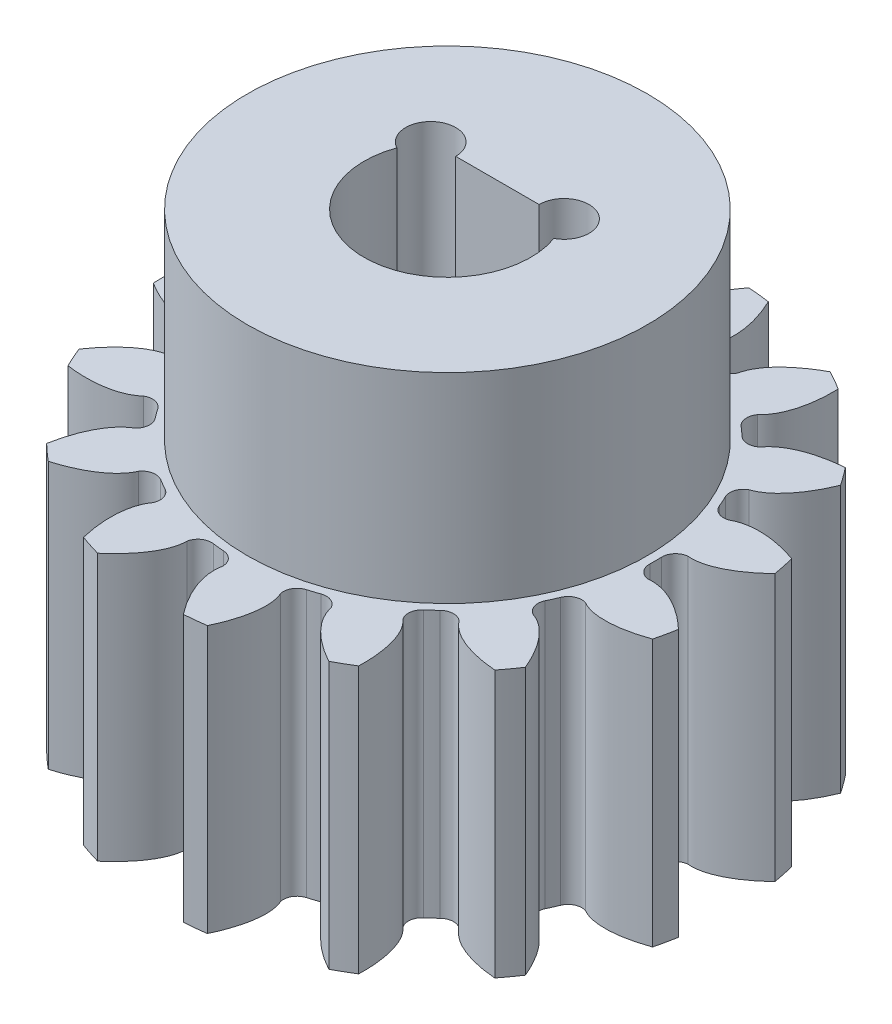
SolidWorks part; units mm, degrees
ref_plane "Front Plane" through (0, 0, 0) normal (0, 0, 1) x (1, 0, 0)
ref_plane "Top Plane" through (0, 0, 0) normal (0, 1, 0) x (1, 0, 0)
ref_plane "Right Plane" through (0, 0, 0) normal (1, 0, 0) x (0, 0, -1)
ref_plane "Plane1" through (0, -8, 0) normal (0, -1, 0) x (1, 0, 0)
sketch "Sketch1" plane through (0, -8, 0) normal (0, -1, 0) x (1, 0, 0)
  arc A0 (-0.8279, 6.1949) -> (-1.2849, 6.5225) centre (-0.8822, 6.6017) cw
  arc A1 (-2.3127, 8.1793) -> (-2.9366, 7.9766) centre (0, 0) ccw
  arc A2 (-2.7943, 6.0321) -> (-2.9715, 5.4984) centre (-3.1666, 5.8594) cw
  arc A3 (-2.9715, 5.4984) -> (-3.276, 5.3226) centre (0, 0) ccw
  arc A4 (-3.276, 5.3226) -> (-3.8268, 5.436) centre (-3.4911, 5.6721) cw
  arc A5 (-5.4396, 6.5315) -> (-5.9271, 6.0925) centre (0, 0) ccw
  arc A6 (-5.0062, 4.374) -> (-4.951, 3.8144) centre (-5.2761, 4.0649) cw
  arc A7 (-4.951, 3.8144) -> (-5.1577, 3.53) centre (0, 0) ccw
  arc A8 (-5.1577, 3.53) -> (-5.7069, 3.4095) centre (-5.4963, 3.7618) cw
  arc A9 (-7.6259, 3.7543) -> (-7.8928, 3.155) centre (0, 0) ccw
  arc A10 (-6.3525, 1.9596) -> (-6.0745, 1.4709) centre (-6.4733, 1.5675) cw
  arc A11 (-6.0745, 1.4709) -> (-6.1476, 1.127) centre (0, 0) ccw
  arc A12 (-6.1476, 1.127) -> (-6.6003, 0.7936) centre (-6.5512, 1.201) cw
  arc A13 (-8.4937, 0.328) -> (-8.4937, -0.328) centre (0, 0) ccw
  arc A14 (-6.6003, -0.7936) -> (-6.1476, -1.127) centre (-6.5512, -1.201) cw
  arc A15 (-6.1476, -1.127) -> (-6.0745, -1.4709) centre (0, 0) ccw
  arc A16 (-6.0745, -1.4709) -> (-6.3525, -1.9596) centre (-6.4733, -1.5675) cw
  arc A17 (-7.8928, -3.155) -> (-7.6259, -3.7543) centre (0, 0) ccw
  arc A18 (-5.7069, -3.4095) -> (-5.1577, -3.53) centre (-5.4963, -3.7618) cw
  arc A19 (-5.1577, -3.53) -> (-4.951, -3.8144) centre (0, 0) ccw
  arc A20 (-4.951, -3.8144) -> (-5.0062, -4.374) centre (-5.2761, -4.0649) cw
  arc A21 (-5.9271, -6.0925) -> (-5.4396, -6.5315) centre (0, 0) ccw
  arc A22 (-3.8268, -5.436) -> (-3.276, -5.3226) centre (-3.4911, -5.6721) cw
  arc A23 (-3.276, -5.3226) -> (-2.9715, -5.4984) centre (0, 0) ccw
  arc A24 (-2.9715, -5.4984) -> (-2.7943, -6.0321) centre (-3.1666, -5.8594) cw
  arc A25 (-2.9366, -7.9766) -> (-2.3127, -8.1793) centre (0, 0) ccw
  arc A26 (-1.2849, -6.5225) -> (-0.8279, -6.1949) centre (-0.8822, -6.6017) cw
  arc A27 (-0.8279, -6.1949) -> (-0.4782, -6.2317) centre (0, 0) ccw
  arc A28 (-0.4782, -6.2317) -> (-0.0993, -6.6471) centre (-0.5096, -6.6408) cw
  arc A29 (0.5616, -8.4814) -> (1.214, -8.4129) centre (0, 0) ccw
  arc A30 (1.4791, -6.4812) -> (1.7634, -5.9961) centre (1.8792, -6.3898) cw
  arc A31 (1.7634, -5.9961) -> (2.0978, -5.8874) centre (0, 0) ccw
  arc A32 (2.0978, -5.8874) -> (2.6129, -6.1128) centre (2.2355, -6.274) cw
  arc A33 (3.9628, -7.5197) -> (4.5309, -7.1917) centre (0, 0) ccw
  arc A34 (3.9874, -5.3193) -> (4.0498, -4.7605) centre (4.3157, -5.073) cw
  arc A35 (4.0498, -4.7605) -> (4.3111, -4.5252) centre (0, 0) ccw
  arc A36 (4.3111, -4.5252) -> (4.8733, -4.5216) centre (4.5941, -4.8223) cw
  arc A37 (6.6787, -5.2578) -> (7.0643, -4.7271) centre (0, 0) ccw
  arc A38 (5.8062, -3.2376) -> (5.6359, -2.7017) centre (6.0059, -2.8791) cw
  arc A39 (5.6359, -2.7017) -> (5.7789, -2.3805) centre (0, 0) ccw
  arc A40 (5.7789, -2.3805) -> (6.2911, -2.1485) centre (6.1583, -2.5368) cw
  arc A41 (8.2399, -2.0868) -> (8.3763, -1.4451) centre (0, 0) ccw
  arc A42 (6.6211, -0.5961) -> (6.2475, -0.1758) centre (6.6577, -0.1873) cw
  arc A43 (6.2475, -0.1758) -> (6.2475, 0.1758) centre (0, 0) ccw
  arc A44 (6.2475, 0.1758) -> (6.6211, 0.5961) centre (6.6577, 0.1873) cw
  arc A45 (8.3763, 1.4451) -> (8.2399, 2.0868) centre (0, 0) ccw
  arc A46 (6.2911, 2.1485) -> (5.7789, 2.3805) centre (6.1583, 2.5368) cw
  arc A47 (5.7789, 2.3805) -> (5.6359, 2.7017) centre (0, 0) ccw
  arc A48 (5.6359, 2.7017) -> (5.8062, 3.2376) centre (6.0059, 2.8791) cw
  arc A49 (7.0643, 4.7271) -> (6.6787, 5.2578) centre (0, 0) ccw
  arc A50 (4.8733, 4.5216) -> (4.3111, 4.5252) centre (4.5941, 4.8223) cw
  arc A51 (4.3111, 4.5252) -> (4.0498, 4.7605) centre (0, 0) ccw
  arc A52 (4.0498, 4.7605) -> (3.9874, 5.3193) centre (4.3157, 5.073) cw
  arc A53 (4.5309, 7.1917) -> (3.9628, 7.5197) centre (0, 0) ccw
  arc A54 (2.6129, 6.1128) -> (2.0978, 5.8874) centre (2.2355, 6.274) cw
  arc A55 (2.0978, 5.8874) -> (1.7634, 5.9961) centre (0, 0) ccw
  arc A56 (1.7634, 5.9961) -> (1.4791, 6.4812) centre (1.8792, 6.3898) cw
  arc A57 (1.214, 8.4129) -> (0.5616, 8.4814) centre (0, 0) ccw
  arc A58 (-0.0993, 6.6471) -> (-0.4782, 6.2317) centre (-0.5096, 6.6408) cw
  arc A59 (-0.4782, 6.2317) -> (-0.8279, 6.1949) centre (0, 0) ccw
  ellipse E0 centre (-3.7721, 7.5173) end of major axis (-6.1606, 8.8992) minor radius 1.3852 (-1.2849, 6.5225) -> (-2.3127, 8.1793) ccw
  ellipse E1 centre (-1.3668, 8.2988) end of major axis (-0.2467, 10.8207) minor radius 1.3852 (-2.9366, 7.9766) -> (-2.7943, 6.0321) ccw
  ellipse E2 centre (-6.5036, 5.3331) end of major axis (-9.2477, 5.624) minor radius 1.3852 (-3.8268, 5.436) -> (-5.4396, 6.5315) ccw
  ellipse E3 centre (-4.6241, 7.0254) end of major axis (-4.6266, 9.7849) minor radius 1.3852 (-5.9271, 6.0925) -> (-5.0062, 4.374) ccw
  ellipse E4 centre (-8.1105, 2.2268) end of major axis (-5.4853, 3.0772) minor radius 1.3852 (-5.7069, 3.4095) -> (-7.6259, 3.7543) ccw
  ellipse E5 centre (-7.0818, 4.5372) end of major axis (-8.2065, 7.0571) minor radius 1.3852 (-7.8928, 3.155) -> (-6.3525, 1.9596) ccw
  ellipse E6 centre (-8.315, -1.2645) end of major axis (-6.2627, 0.5801) minor radius 1.3852 (-6.6003, 0.7936) -> (-8.4937, 0.328) ccw
  ellipse E7 centre (-8.315, 1.2645) end of major axis (-10.3674, 3.1091) minor radius 1.3852 (-8.4937, -0.328) -> (-6.6003, -0.7936) ccw
  ellipse E8 centre (-7.0818, -4.5372) end of major axis (-8.2065, -7.0571) minor radius 1.3852 (-6.3525, -1.9596) -> (-7.8928, -3.155) ccw
  ellipse E9 centre (-8.1105, -2.2268) end of major axis (-10.7357, -1.3765) minor radius 1.3852 (-7.6259, -3.7543) -> (-5.7069, -3.4095) ccw
  ellipse E10 centre (-4.6241, -7.0254) end of major axis (-4.6266, -9.7849) minor radius 1.3852 (-5.0062, -4.374) -> (-5.9271, -6.0925) ccw
  ellipse E11 centre (-6.5036, -5.3331) end of major axis (-9.2477, -5.624) minor radius 1.3852 (-5.4396, -6.5315) -> (-3.8268, -5.436) ccw
  ellipse E12 centre (-1.3668, -8.2988) end of major axis (-2.4869, -5.7769) minor radius 1.3852 (-2.7943, -6.0321) -> (-2.9366, -7.9766) ccw
  ellipse E13 centre (-3.7721, -7.5173) end of major axis (-1.3836, -6.1354) minor radius 1.3852 (-2.3127, -8.1793) -> (-1.2849, -6.5225) ccw
  ellipse E14 centre (2.1268, -8.1373) end of major axis (4.1758, -9.9856) minor radius 1.3852 (-0.0993, -6.6471) -> (0.5616, -8.4814) ccw
  ellipse E15 centre (-0.3884, -8.4016) end of major axis (1.2315, -6.1677) minor radius 1.3852 (1.214, -8.4129) -> (1.4791, -6.4812) ccw
  ellipse E16 centre (5.2526, -6.5688) end of major axis (7.8763, -7.4238) minor radius 1.3852 (2.6129, -6.1128) -> (3.9628, -7.5197) ccw
  ellipse E17 centre (3.0624, -7.8333) end of major axis (3.6337, -5.1336) minor radius 1.3852 (4.5309, -7.1917) -> (3.9874, -5.3193) ccw
  ellipse E18 centre (7.4703, -3.8644) end of major axis (10.2149, -3.5785) minor radius 1.3852 (4.8733, -4.5216) -> (6.6787, -5.2578) ccw
  ellipse E19 centre (5.9837, -5.9105) end of major axis (5.4076, -3.2118) minor radius 1.3852 (7.0643, -4.7271) -> (5.8062, -3.2376) ccw
  ellipse E20 centre (8.3962, -0.4919) end of major axis (10.7872, 0.8857) minor radius 1.3852 (6.2911, -2.1485) -> (8.2399, -2.0868) ccw
  ellipse E21 centre (7.8704, -2.9657) end of major axis (6.2464, -0.7347) minor radius 1.3852 (8.3763, -1.4451) -> (6.6211, -0.5961) ccw
  ellipse E22 centre (7.8704, 2.9657) end of major axis (6.2464, 0.7347) minor radius 1.3852 (6.6211, 0.5961) -> (8.3763, 1.4451) ccw
  ellipse E23 centre (8.3962, 0.4919) end of major axis (10.7872, -0.8857) minor radius 1.3852 (8.2399, 2.0868) -> (6.2911, 2.1485) ccw
  ellipse E24 centre (5.9837, 5.9105) end of major axis (6.5599, 8.6091) minor radius 1.3852 (5.8062, 3.2376) -> (7.0643, 4.7271) ccw
  ellipse E25 centre (7.4703, 3.8644) end of major axis (10.2149, 3.5785) minor radius 1.3852 (6.6787, 5.2578) -> (4.8733, 4.5216) ccw
  ellipse E26 centre (3.0624, 7.8333) end of major axis (3.6337, 5.1336) minor radius 1.3852 (3.9874, 5.3193) -> (4.5309, 7.1917) ccw
  ellipse E27 centre (5.2526, 6.5688) end of major axis (7.8763, 7.4238) minor radius 1.3852 (3.9628, 7.5197) -> (2.6129, 6.1128) ccw
  ellipse E28 centre (-0.3884, 8.4016) end of major axis (1.2315, 6.1677) minor radius 1.3852 (1.4791, 6.4812) -> (1.214, 8.4129) ccw
  ellipse E29 centre (2.1268, 8.1373) end of major axis (4.1758, 9.9856) minor radius 1.3852 (0.5616, 8.4814) -> (-0.0993, 6.6471) ccw
  point P3 (-3.7721, 7.5173)
  point P4 (-1.3836, 6.1354)
  point P5 (-4.4658, 6.3183)
  point P6 (-1.2849, 6.5225)
  point P7 (-2.3127, 8.1793)
  point P8 (-1.6162, 7.4233)
  point P9 (-5.928, 7.6113)
  point P18 (-1.3668, 8.2988)
  point P19 (-0.1009, 7.7365)
  point P20 (-0.2467, 10.8207)
  point P21 (-2.9366, 7.9766)
  point P22 (-2.7943, 6.0321)
  point P23 (-3.0557, 6.9555)
  point P24 (0.3221, 9.6421)
  point P36 (-6.5036, 5.3331)
  point P37 (-3.7595, 5.0422)
  point P38 (-6.6496, 3.9556)
  point P39 (-3.8268, 5.436)
  point P40 (-5.4396, 6.5315)
  point P41 (-4.4958, 6.1241)
  point P42 (-8.5113, 4.5421)
  point P50 (-4.6241, 7.0254)
  point P51 (-3.2389, 7.0266)
  point P52 (-4.6266, 9.7849)
  point P53 (-5.9271, 6.0925)
  point P54 (-5.0062, 4.374)
  point P55 (-5.6206, 5.1113)
  point P56 (-3.6276, 8.9395)
  point P68 (-8.1105, 2.2268)
  point P69 (-5.4853, 3.0772)
  point P70 (-7.6836, 0.909)
  point P71 (-5.7069, 3.4095)
  point P72 (-7.6259, 3.7543)
  point P73 (-6.598, 3.7661)
  point P74 (-9.6229, 0.6876)
  point P82 (-7.0818, 4.5372)
  point P83 (-5.8169, 5.1018)
  point P84 (-8.2065, 7.0571)
  point P85 (-7.8928, 3.155)
  point P86 (-6.3525, 1.9596)
  point P87 (-7.2137, 2.3833)
  point P88 (-6.95, 6.6912)
  point P100 (-8.315, -1.2645)
  point P101 (-6.2627, 0.5801)
  point P102 (-7.3891, -2.2948)
  point P103 (-6.6003, 0.7936)
  point P104 (-8.4937, 0.328)
  point P105 (-7.5594, 0.7568)
  point P106 (-9.0706, -3.2859)
  point P114 (-8.315, 1.2645)
  point P115 (-6.2627, -0.5801)
  point P116 (-7.3891, 2.2948)
  point P117 (-8.4937, -0.328)
  point P118 (-6.6003, -0.7936)
  point P119 (-7.5594, -0.7568)
  point P120 (-9.0706, 3.2859)
  point P132 (-7.0818, -4.5372)
  point P133 (-5.8169, -5.1018)
  point P134 (-8.2065, -7.0571)
  point P135 (-6.3525, -1.9596)
  point P136 (-7.8928, -3.155)
  point P137 (-7.2137, -2.3833)
  point P138 (-6.95, -6.6912)
  point P146 (-8.1105, -2.2268)
  point P147 (-5.4853, -3.0772)
  point P148 (-7.6836, -0.909)
  point P149 (-7.6259, -3.7543)
  point P150 (-5.7069, -3.4095)
  point P151 (-6.598, -3.7661)
  point P152 (-9.6229, -0.6876)
  point P164 (-4.6241, -7.0254)
  point P165 (-3.2389, -7.0266)
  point P166 (-4.6266, -9.7849)
  point P167 (-5.0062, -4.374)
  point P168 (-5.9271, -6.0925)
  point P169 (-5.6206, -5.1113)
  point P170 (-3.6276, -8.9395)
  point P178 (-6.5036, -5.3331)
  point P179 (-3.7595, -5.0422)
  point P180 (-6.6496, -3.9556)
  point P181 (-5.4396, -6.5315)
  point P182 (-3.8268, -5.436)
  point P183 (-4.4958, -6.1241)
  point P184 (-8.5113, -4.5421)
  point P196 (-1.3668, -8.2988)
  point P197 (-0.1009, -7.7365)
  point P198 (-0.2467, -10.8207)
  point P199 (-2.7943, -6.0321)
  point P200 (-2.9366, -7.9766)
  point P201 (-3.0557, -6.9555)
  point P202 (0.3221, -9.6421)
  point P210 (-3.7721, -7.5173)
  point P211 (-1.3836, -6.1354)
  point P212 (-4.4658, -6.3183)
  point P213 (-2.3127, -8.1793)
  point P214 (-1.2849, -6.5225)
  point P215 (-1.6162, -7.4233)
  point P216 (-5.928, -7.6113)
  point P228 (2.1268, -8.1373)
  point P229 (4.1758, -9.9856)
  point P230 (1.1989, -9.1659)
  point P231 (-0.0993, -6.6471)
  point P232 (0.5616, -8.4814)
  point P233 (0.0375, -7.5971)
  point P234 (4.216, -8.6775)
  point P242 (-0.3884, -8.4016)
  point P243 (0.7329, -9.2148)
  point P244 (1.2315, -6.1677)
  point P245 (1.214, -8.4129)
  point P246 (1.4791, -6.4812)
  point P247 (1.5428, -7.4389)
  point P248 (-2.3197, -9.3644)
  point P260 (5.2526, -6.5688)
  point P261 (7.8763, -7.4238)
  point P262 (4.8234, -7.8858)
  point P263 (2.6129, -6.1128)
  point P264 (3.9628, -7.5197)
  point P265 (3.1243, -6.925)
  point P266 (7.381, -6.2125)
  point P274 (3.0624, -7.8333)
  point P275 (4.4176, -8.1201)
  point P276 (3.6337, -5.1336)
  point P277 (4.5309, -7.1917)
  point P278 (3.9874, -5.3193)
  point P279 (4.4351, -6.1682)
  point P280 (1.6897, -9.4983)
  point P292 (7.4703, -3.8644)
  point P293 (10.2149, -3.5785)
  point P294 (7.6138, -5.2422)
  point P295 (4.8733, -4.5216)
  point P296 (6.6787, -5.2578)
  point P297 (5.6708, -5.0556)
  point P298 (9.2697, -2.6733)
  point P306 (5.9837, -5.9105)
  point P307 (7.3384, -5.6212)
  point P308 (5.4076, -3.2118)
  point P309 (7.0643, -4.7271)
  point P310 (5.8062, -3.2376)
  point P311 (6.5605, -3.831)
  point P312 (5.4069, -7.9899)
  point P324 (8.3962, -0.4919)
  point P325 (10.7872, 0.8857)
  point P326 (9.0877, -1.6921)
  point P327 (6.2911, -2.1485)
  point P328 (8.2399, -2.0868)
  point P329 (7.2368, -2.312)
  point P330 (9.5556, 1.3282)
  point P338 (7.8704, -2.9657)
  point P339 (8.9903, -2.1505)
  point P340 (6.2464, -0.7347)
  point P341 (8.3763, -1.4451)
  point P342 (6.6211, -0.5961)
  point P343 (7.5515, -0.8314)
  point P344 (8.1893, -5.1)
  point P356 (7.8704, 2.9657)
  point P357 (8.9903, 2.1505)
  point P358 (6.2464, 0.7347)
  point P359 (6.6211, 0.5961)
  point P360 (8.3763, 1.4451)
  point P361 (7.5515, 0.8314)
  point P362 (8.1893, 5.1)
  point P370 (8.3962, 0.4919)
  point P371 (10.7872, -0.8857)
  point P372 (9.0877, 1.6921)
  point P373 (8.2399, 2.0868)
  point P374 (6.2911, 2.1485)
  point P375 (7.2368, 2.312)
  point P376 (9.5556, -1.3282)
  point P388 (5.9837, 5.9105)
  point P389 (7.3384, 5.6212)
  point P390 (5.4076, 3.2118)
  point P391 (5.8062, 3.2376)
  point P392 (7.0643, 4.7271)
  point P393 (6.5605, 3.831)
  point P394 (5.4069, 7.9899)
  point P402 (7.4703, 3.8644)
  point P403 (10.2149, 3.5785)
  point P404 (7.6138, 5.2422)
  point P405 (6.6787, 5.2578)
  point P406 (4.8733, 4.5216)
  point P407 (5.6708, 5.0556)
  point P408 (9.2697, 2.6733)
  point P420 (3.0624, 7.8333)
  point P421 (4.4176, 8.1201)
  point P422 (3.6337, 5.1336)
  point P423 (3.9874, 5.3193)
  point P424 (4.5309, 7.1917)
  point P425 (4.4351, 6.1682)
  point P426 (1.6897, 9.4983)
  point P434 (5.2526, 6.5688)
  point P435 (7.8763, 7.4238)
  point P436 (4.8234, 7.8858)
  point P437 (3.9628, 7.5197)
  point P438 (2.6129, 6.1128)
  point P439 (3.1243, 6.925)
  point P440 (7.381, 6.2125)
  point P452 (-0.3884, 8.4016)
  point P453 (0.7329, 9.2148)
  point P454 (1.2315, 6.1677)
  point P455 (1.4791, 6.4812)
  point P456 (1.214, 8.4129)
  point P457 (1.5428, 7.4389)
  point P458 (-2.3197, 9.3644)
  point P466 (2.1268, 8.1373)
  point P467 (4.1758, 9.9856)
  point P468 (1.1989, 9.1659)
  point P469 (0.5616, 8.4814)
  point P470 (-0.0993, 6.6471)
  point P471 (0.0375, 7.5971)
  point P472 (4.216, 8.6775)
extrude "Boss-Extrude1" add sketch "Sketch1" against normal blind 8
sketch "Sketch3" plane through (0, 0, 0) normal (0, 1, 0) x (1, 0, 0)
  circle A0 centre (0, 0) radius 6
  dimension "D1" = 12
extrude "Boss-Extrude2" add sketch "Sketch3" along normal blind 6
sketch "Sketch4" plane through (0, 6, 0) normal (0, 1, 0) x (1, 0, 0)
  line L0 (-2, 1.5) -> (2, 1.5)
  arc A0 (-2, 1.5) -> (2, 1.5) centre (0, 0) ccw
  dimension "D1" = 5
  dimension "D2" = 4
extrude "Cut-Extrude1" cut sketch "Sketch4" against normal through all
sketch "Sketch5" plane through (0, 6, 0) normal (0, 1, 0) x (1, 0, 0)
  circle A0 centre (-2, 1.5) radius 0.75
  circle A1 centre (2, 1.5) radius 0.75
  dimension "D1" = 1.5
  dimension "D2" = 1.5
extrude "Cut-Extrude2" cut sketch "Sketch5" against normal through all
